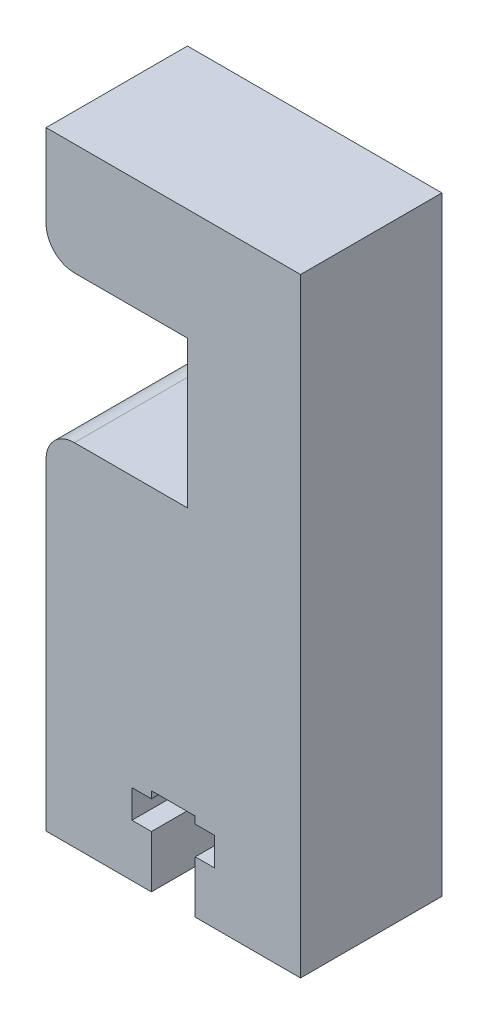
SolidWorks part; units mm, degrees
ref_plane "Płaszczyzna przednia" through (0, 0, 0) normal (0, 0, 1) x (1, 0, 0)
ref_plane "Płaszczyzna górna" through (0, 0, 0) normal (0, 1, 0) x (1, 0, 0)
ref_plane "Płaszczyzna prawa" through (0, 0, 0) normal (1, 0, 0) x (0, 0, -1)
sketch "Szkic1" plane through (0, 0, 0) normal (0, 0, 1) x (1, 0, 0)
  line L1 (-39.1463, 3.9) -> (-57.1463, 3.9)
  line L2 (-39.1463, 3.9) -> (-39.1463, 47)
  line L3 (-57.1463, 3.9) -> (-57.1463, 26.7)
  line L4 (-39.1463, 47) -> (-57.1463, 47)
  line L8 (-55.1463, 39.1) -> (-47.1463, 39.1)
  line L9 (-55.1463, 28.7) -> (-47.1463, 28.7)
  line L10 (-47.1463, 39.1) -> (-47.1463, 28.7)
  line L11 (-57.1463, 41.1) -> (-57.1463, 47)
  arc A0 (-57.1463, 26.7) -> (-55.1463, 28.7) centre (-55.1463, 26.7) cw
  arc A1 (-55.1463, 39.1) -> (-57.1463, 41.1) centre (-55.1463, 41.1) cw
  point P9 (-57.1463, 39.1)
  dimension "D6" = 2
  dimension "D1" = 24.8
  dimension "D2" = 18
  dimension "D3" = 10
  dimension "D4" = 10.4
  dimension "D5" = 7.9
extrude "Dodanie-wyciągnięcie1" add sketch "Szkic1" along normal blind 10
sketch "Szkic2" plane through (0, 0, 10) normal (0, 0, 1) x (1, 0, 0)
  line L0 (-46.5963, 3.9) -> (-46.5963, 7.6)
  line L1 (-46.5963, 3.9) -> (-49.6963, 3.9)
  line L2 (-46.5963, 10.1) -> (-49.6963, 10.1)
  line L3 (-49.6963, 3.9) -> (-49.6963, 7.6)
  line L4 (-57.1463, 3.9) -> (-39.1463, 3.9) construction
  line L5 (-45.2213, 7.6) -> (-45.2213, 9.6)
  line L6 (-45.2213, 7.6) -> (-46.5963, 7.6)
  line L7 (-45.2213, 9.6) -> (-46.5963, 9.6)
  line L8 (-51.0713, 7.6) -> (-51.0713, 9.6)
  line L9 (-49.6963, 7.6) -> (-51.0713, 7.6)
  line L10 (-46.5963, 9.6) -> (-46.5963, 10.1)
  line L11 (-49.6963, 9.6) -> (-51.0713, 9.6)
  line L12 (-49.6963, 9.6) -> (-49.6963, 10.1)
  line L13 (-57.1463, 26.7) -> (-57.1463, 3.9) construction
  point P14 (-48.1463, 3.9)
  dimension "D1" = 6.2
  dimension "D2" = 3.1
  dimension "D3" = 5.85
  dimension "D4" = 2
  dimension "D5" = 0.5
  dimension "D6" = 9
  dimension "D7" = 1.375
extrude "Wytnij-wyciągnięcie1" cut sketch "Szkic2" against normal blind 10
equation "\"tolerancja_wpusy\"=0.2"
equation "\"dlugosc_wpustu_duzy\"=20"
equation "\"srednica_otworu_M3\"=3.1"
equation "\"szerokosc_nogi_T\"=3.1"
equation "\"dlugosc_T_30\"=11"
equation "\"grubosc_na_nakretke_kwadrat\"=2"
equation "\"szerokosc_na_nakretke_kwadrat\"=5.85"
equation "\"wyokosc_nadstawki_T\"=0.5"
equation "\"dlugosc_T_20_6\"=14"
equation "\"D2@Szkic2\"=\"szerokosc_nogi_T\""
equation "\"D3@Szkic2\"=\"szerokosc_na_nakretke_kwadrat\""
equation "\"D4@Szkic2\"=\"grubosc_na_nakretke_kwadrat\""
equation "\"D5@Szkic2\"=\"wyokosc_nadstawki_T\""
equation "\"D7@Szkic2\"=(\"szerokosc_na_nakretke_kwadrat\"-\"szerokosc_nogi_T\")/2"
